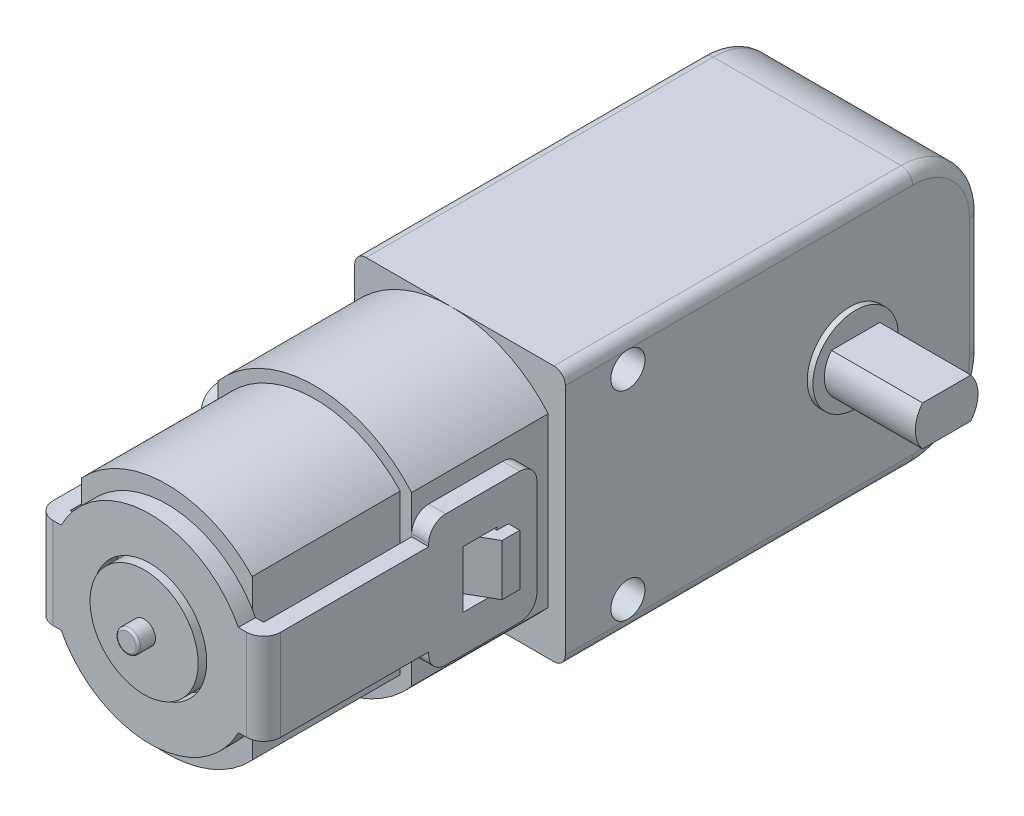
SolidWorks part; units mm, degrees
ref_plane "Plano frontal" through (0, 0, 0) normal (0, 0, 1) x (1, 0, 0)
ref_plane "Plano superior" through (0, 0, 0) normal (0, 1, 0) x (1, 0, 0)
ref_plane "Plano direito" through (0, 0, 0) normal (1, 0, 0) x (0, 0, -1)
sketch "Esboço1" plane through (0, 0, 0) normal (1, 0, 0) x (0, 0, -1)
  line L0 (0, 0) -> (0, 50000) construction
  line L1 (11.5, 11.25) -> (-25, 11.25)
  line L2 (11.5, 11.25) -> (11.5, -11.25)
  line L3 (11.5, -11.25) -> (-25, -11.25)
  line L4 (-25, 11.25) -> (-25, -11.25)
  line L5 (0, 0) -> (50000, 0) construction
  dimension "D1" = 22.5
  dimension "D2" = 11.5
  dimension "D3" = 36.5
extrude "Ressalto-extrusão1" add sketch "Esboço1" along normal mid plane 18.5
fillet "Filete1" radius 6 2 edges at (0, -11.25, -11.5) (0, 11.25, -11.5)
sketch "Esboço2" plane through (0, 0, 25) normal (0, 0, 1) x (1, 0, 0)
  line L0 (0, 0) -> (0, 50000) construction
  line L1 (0, 0) -> (50000, 0) construction
  line L2 (9.25, -11.25) -> (-9.25, -11.25) construction
  line L3 (9.25, 11.25) -> (-9.25, 11.25) construction
  line L4 (7.75, 7.3697) -> (7.75, -7.3697)
  line L5 (-9.25, -7.3697) -> (-9.25, 7.3697)
  line L6 (-9.25, 11.25) -> (-9.25, -11.25) construction
  line L7 (9.25, 11.25) -> (9.25, -11.25) construction
  arc A0 (-9.25, -7.3697) -> (7.75, -7.3697) centre (-0.75, 0) ccw
  arc A1 (7.75, 7.3697) -> (-9.25, 7.3697) centre (-0.75, 0) ccw
  dimension "D1" = 1.5
extrude "Ressalto-extrusão2" add sketch "Esboço2" along normal blind 12
sketch "Esboço3" plane through (0, 0, 37) normal (0, 0, 1) x (1, 0, 0)
  line L0 (-8.25, 6.9866) -> (-8.25, -6.9866)
  line L1 (6.75, -6.9866) -> (6.75, 6.9866)
  line L2 (-9.25, 7.3697) -> (-9.25, -7.3697)
  line L3 (7.75, -7.3697) -> (7.75, 7.3697)
  line L4 (-9.25, 7.3697) -> (-9.25, -7.3697) construction
  line L5 (7.75, -7.3697) -> (7.75, 7.3697) construction
  arc A0 (-8.25, -6.9866) -> (6.75, -6.9866) centre (-0.75, 0) ccw
  arc A1 (6.75, 6.9866) -> (-8.25, 6.9866) centre (-0.75, 0) ccw
  arc A2 (7.75, 7.3697) -> (-9.25, 7.3697) centre (-0.75, 0) ccw
  arc A3 (-9.25, -7.3697) -> (7.75, -7.3697) centre (-0.75, 0) ccw
  arc A4 (7.75, 7.3697) -> (-9.25, 7.3697) centre (-0.75, 0) ccw construction
  arc A5 (-9.25, -7.3697) -> (7.75, -7.3697) centre (-0.75, 0) ccw construction
  dimension "D1" = 0
  dimension "D2" = 1
extrude "Ressalto-extrusão3" add sketch "Esboço3" along normal blind 13
sketch "Esboço4" plane through (9.25, 0, 0) normal (1, 0, 0) x (0, 0, -1)
  circle A0 centre (0, 0) radius 3.75
  dimension "D1" = 7.5
extrude "Ressalto-extrusão4" add sketch "Esboço4" along normal blind 0.5
sketch "Esboço5" plane through (7.75, 0, 0) normal (1, 0, 0) x (0, 0, -1)
  line L0 (-37, -7.3697) -> (-37, 7.3697) construction
  line L1 (-27.5, 5.75) -> (-37, 5.75)
  line L2 (-27.5, 5.75) -> (-27.5, -5.75)
  line L3 (-27.5, -5.75) -> (-37, -5.75)
  line L4 (-37, 5.75) -> (-37, -5.75)
  line L5 (0, 0) -> (-50000, 0) construction
  line L6 (0, 0) -> (0, 50000) construction
  line L7 (-25, 11.25) -> (-25, -11.25) construction
  dimension "D1" = 2.5
  dimension "D2" = 11.5
extrude "Ressalto-extrusão5" add sketch "Esboço5" along normal blind 1.5 separate body
sketch "Esboço6" plane through (0, 0, 37) normal (0, 0, 1) x (1, 0, 0)
  line L0 (9.25, 5.75) -> (9.25, -5.75) construction
  line L1 (9.25, 4) -> (7.75, 4)
  line L2 (9.25, 4) -> (9.25, -4)
  line L3 (9.25, -4) -> (7.75, -4)
  line L4 (7.75, 4) -> (7.75, -4)
  line L5 (7.75, -7.3697) -> (7.75, 7.3697) construction
  line L6 (0, 0) -> (-50000, 0) construction
  dimension "D1" = 8
extrude "Ressalto-extrusão6" add sketch "Esboço6" along normal up to surface (13 mm away) up to face at (-0.75, 0, 50)
sketch "Esboço7" plane through (0, 0, 50) normal (0, 0, 1) x (1, 0, 0)
  line L0 (9.25, 4) -> (7.0322, 4)
  line L1 (9.25, 4) -> (9.25, -4)
  line L2 (9.25, -4) -> (7.0322, -4)
  line L3 (-0.75, 8.75) -> (-0.75, 0) construction
  line L4 (-10.75, -4) -> (-8.5322, -4)
  line L5 (-10.75, 4) -> (-10.75, -4)
  line L6 (-10.75, 4) -> (-8.5322, 4)
  arc A0 (7.0322, 4) -> (-8.5322, 4) centre (-0.75, 0) ccw
  arc A1 (6.75, 6.9866) -> (-8.25, 6.9866) centre (-0.75, 0) ccw construction
  arc A2 (-8.5322, -4) -> (7.0322, -4) centre (-0.75, 0) ccw
  circle A3 centre (-0.75, 0) radius 5
  dimension "D1" = 17.5
  dimension "D2" = 10
sketch "Esboço8" plane through (0, 0, 50) normal (0, 0, 1) x (1, 0, 0)
  circle A0 centre (-0.75, 0) radius 4.75
  dimension "D1" = 9.5
extrude "Ressalto-extrusão7" add sketch "Esboço8" along normal blind 2
extrude "Ressalto-extrusão8" add sketch "Esboço7" along normal blind 1.5
ref_plane "Plano1" through (-0.75, 8.75, 51.5) normal (-1, 0, 0) x (0, 0, 1)
sketch "Esboço10" plane through (0, 0, 50) normal (0, 0, -1) x (-1, 0, 0)
  line L0 (10.75, -4) -> (8.5322, -4) construction
  line L1 (10.75, 4) -> (9.25, 4)
  line L2 (10.75, 4) -> (10.75, -4)
  line L3 (10.75, -4) -> (9.25, -4)
  line L4 (9.25, 4) -> (9.25, -4)
  line L5 (-9.25, 4) -> (-7.75, 4) construction
extrude "Ressalto-extrusão9" add sketch "Esboço10" along normal up to surface (13 mm away) up to face at (8.6875, 5.3125, 37)
sketch "Esboço11" plane through (0, 0, 37) normal (0, 0, -1) x (-1, 0, 0)
  line L0 (10.75, -4) -> (10.75, 4) construction
  line L1 (10.75, 5.75) -> (9.25, 5.75)
  line L2 (10.75, 5.75) -> (10.75, -5.75)
  line L3 (10.75, -5.75) -> (9.25, -5.75)
  line L4 (9.25, 5.75) -> (9.25, -5.75)
  line L5 (9.25, 4) -> (9.25, -4) construction
  line L6 (-9.25, -5.75) -> (-9.25, 5.75) construction
  line L7 (-9.25, 5.75) -> (-7.75, 5.75) construction
extrude "Ressalto-extrusão10" add sketch "Esboço11" along normal up to surface (9.5 mm away) up to face at (8.5, 0, 27.5)
fillet "Filete2" radius 1.5 10 edges at (8.5, -5.75, 37) (8.5, -5.75, 27.5) (8.5, 5.75, 27.5) (8.5, 5.75, 37) (9.25, 0, 51.5) (-10.75, 0, 51.5) (-10, -5.75, 27.5) (-10, -5.75, 37) (-10, 5.75, 37) (-10, 5.75, 27.5)
sketch "Esboço12" plane through (9.25, 0, 0) normal (1, 0, 0) x (0, 0, -1)
  line L0 (-25, 11.25) -> (-25, -11.25) construction
  line L1 (-31, 2.5) -> (-34, 2.5)
  line L2 (-31, 2.5) -> (-31, -2.5)
  line L3 (-31, -2.5) -> (-34, -2.5)
  line L4 (-34, 2.5) -> (-34, -2.5)
  line L5 (0, 0) -> (-50000, 0) construction
  dimension "D1" = 6
  dimension "D2" = 3
  dimension "D3" = 5
extrude "Corte-extrusão1" cut sketch "Esboço12" against normal through all
sketch "Esboço14" plane through (0, 0, 0) normal (0, 1, 0) x (1, 0, 0)
  line L0 (7.75, -33) -> (10.25, -31.5566)
  line L1 (7.75, -37) -> (7.75, -25) construction
  line L2 (10.25, -31.5566) -> (10.25, -30)
  line L3 (10.25, -30) -> (9.25, -30)
  line L4 (9.25, -35.5) -> (9.25, -29) construction
  line L5 (9.25, -30) -> (9.25, -31)
  line L6 (7.75, -31) -> (9.25, -31) construction
  line L7 (9.25, -31) -> (7.75, -31)
  line L8 (7.75, -31) -> (7.75, -33)
  dimension "D1" = 2.5
  dimension "D2" = 1
  dimension "D3" = 60
  dimension "D4" = 2
extrude "Ressalto-extrusão11" add sketch "Esboço14" along normal mid plane 4.5
mirror "Espelhar6" about plane through (-0.75, 8.75, 51.5) normal (-1, 0, 0) of "Ressalto-extrusão11"
sketch "Esboço15" plane through (0, 0, 52) normal (0, 0, 1) x (1, 0, 0)
  circle A0 centre (-0.75, 0) radius 1
  dimension "D1" = 2
extrude "Ressalto-extrusão12" add sketch "Esboço15" along normal blind 1.5
sketch "Esboço16" plane through (9.75, 0, 0) normal (1, 0, 0) x (0, 0, -1)
  line L0 (0, 0) -> (-50000, 0) construction
  line L1 (-2.1213, 1.75) -> (2.1213, 1.75)
  line L3 (2.1213, -1.75) -> (-2.1213, -1.75)
  arc A0 (2.1213, -1.75) -> (2.1213, 1.75) centre (0, 0) ccw
  arc A1 (-2.1213, 1.75) -> (-2.1213, -1.75) centre (0, 0) ccw
  dimension "D1" = 5.5
  dimension "D2" = 3.5
extrude "Ressalto-extrusão13" add sketch "Esboço16" along normal blind 8
fillet "Filete4" radius 1 10 edges at (-9.25, -11.25, 9.75) (9.25, -11.25, 9.75) (9.25, -9.4926, -9.7426) (-9.25, -9.4926, -9.7426) (9.25, 0, -11.5) (-9.25, 0, -11.5) (9.25, 9.4926, -9.7426) (-9.25, 9.4926, -9.7426) (9.25, 11.25, 9.75) (-9.25, 11.25, 9.75)
sketch "Esboço17" plane through (9.25, 0, 0) normal (1, 0, 0) x (0, 0, -1)
  line L0 (-19.5, 8.75) -> (-19.5, -8.75) construction
  line L1 (-19.5, 0) -> (0, 0) construction
  line L2 (-25, 11.25) -> (-25, 7.3697) construction
  circle A0 centre (-19.5, 8.75) radius 1.5
  circle A1 centre (-19.5, -8.75) radius 1.5
  dimension "D2" = 3
  dimension "D3" = 4
  dimension "D1" = 17.5
extrude "Corte-extrusão2" cut sketch "Esboço17" against normal through all
sketch "Esboço19" plane through (0, 0, 0) normal (1, 0, 0) x (0, 0, -1)
  line L0 (11.5, 3) -> (14.4508, 2.459)
  line L1 (11.5, 5.25) -> (11.5, -5.25) construction
  line L2 (14.4508, -2.459) -> (11.5, -3)
  line L3 (11.5, -3) -> (11.5, 3)
  line L4 (0, 0) -> (50000, 0) construction
  arc A0 (14.4508, 2.459) -> (14.4508, -2.459) centre (14, 0) cw
  circle A1 centre (14, 0) radius 1.5
  dimension "D2" = 5
  dimension "D3" = 3
  dimension "D4" = 2.5
  dimension "D1" = 6
extrude "Ressalto-extrusão14" add sketch "Esboço19" along normal mid plane 3
fillet "Filete5" radius 1 2 edges at (0, 3, -11.5) (0, -3, -11.5)
fillet "Filete6" radius 0.2 1 edges at (0.25, 0, 53.5)
sketch "Sketch1" plane through (17.75, 0, 0) normal (1, 0, 0) x (0, 0, -1)
  line L0 (-2.1213, 1.75) -> (2.1213, 1.75)
  line L1 (-2.1213, -1.75) -> (2.1213, -1.75)
  arc A0 (2.1213, 1.75) -> (2.1213, -1.75) centre (-0.0207, 0) cw
  arc A1 (-2.1213, -1.75) -> (-2.1213, 1.75) centre (-0.0171, 0) cw
sketch "Sketch2" plane through (-9.25, 0, 0) normal (-1, 0, 0) x (0, 0, 1)
  circle A0 centre (19.5, -8.75) radius 1.5 construction
  circle A1 centre (19.5, -8.75) radius 1.5
  circle A2 centre (19.5, 8.75) radius 1.5 construction
  circle A3 centre (19.5, 8.75) radius 1.5
